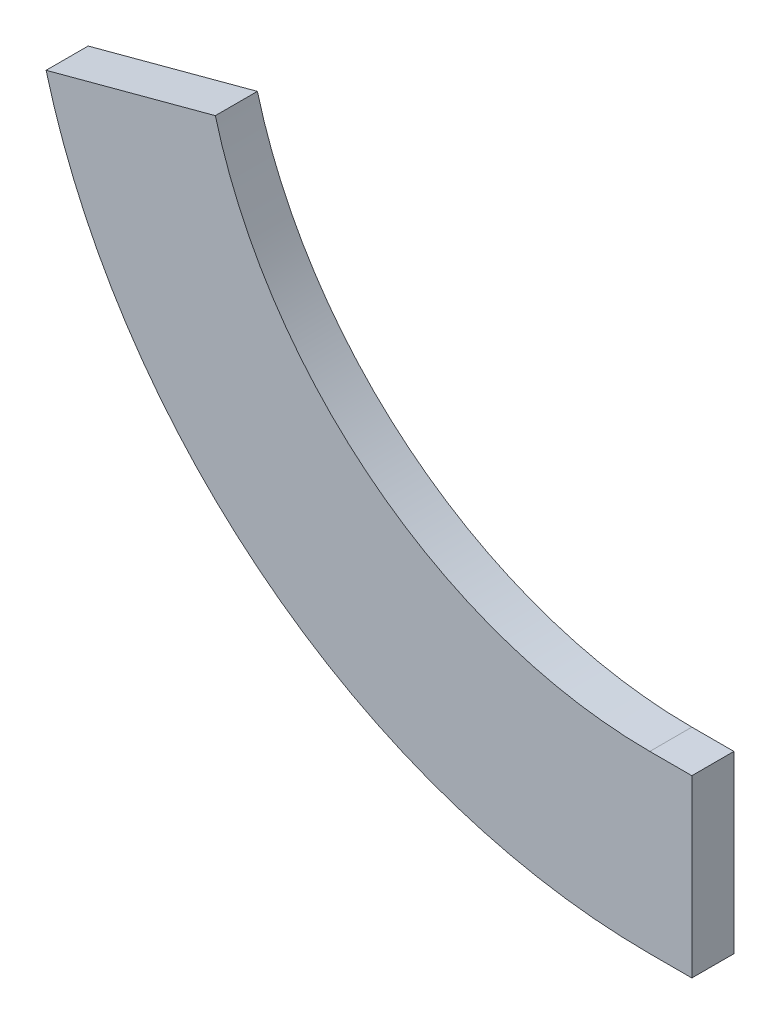
SolidWorks part; units mm, degrees
ref_plane "Front Plane" through (0, 0, 0) normal (0, 0, 1) x (1, 0, 0)
ref_plane "Top Plane" through (0, 0, 0) normal (0, 1, 0) x (1, 0, 0)
ref_plane "Right Plane" through (0, 0, 0) normal (1, 0, 0) x (0, 0, -1)
sketch "Sketch1" plane through (0, 0, 0) normal (0, 0, 1) x (1, 0, 0)
  line L0 (-97.4016, -31.75) -> (-100.4496, -31.75)
  line L1 (-131.9395, -7.587) -> (-144.2068, -10.874)
  line L2 (-100.4496, -44.45) -> (-97.4016, -44.45)
  line L3 (-97.4016, -44.45) -> (-97.4016, -31.75)
  line L4 (-97.4016, -44.704) -> (-97.4016, -31.496) construction
  line L5 (-97.4016, -31.496) -> (-100.4496, -31.496) construction
  line L6 (-97.4016, -44.704) -> (-100.4496, -44.704) construction
  line L7 (-100.4496, -71.9043) -> (-100.4496, -2.54) construction
  line L8 (-100.4496, -71.9043) -> (-100.4496, -2.54) construction
  line L9 (-154.6877, -13.6823) -> (48141.6036, 12927.2699) construction
  arc A0 (-100.4496, -31.75) -> (-131.9395, -7.587) centre (-100.4496, 0.8507) cw
  arc A1 (-144.2068, -10.874) -> (-100.4496, -44.45) centre (-100.4496, 0.8507) ccw
  dimension "D1" = 0.254
  dimension "D2" = 0.254
  dimension "D3" = 12.7
  dimension "D4" = 75
extrude "Boss-Extrude1" add sketch "Sketch1" along normal mid plane 3.048 contours A0 L1 A1 L2 L3 L0
